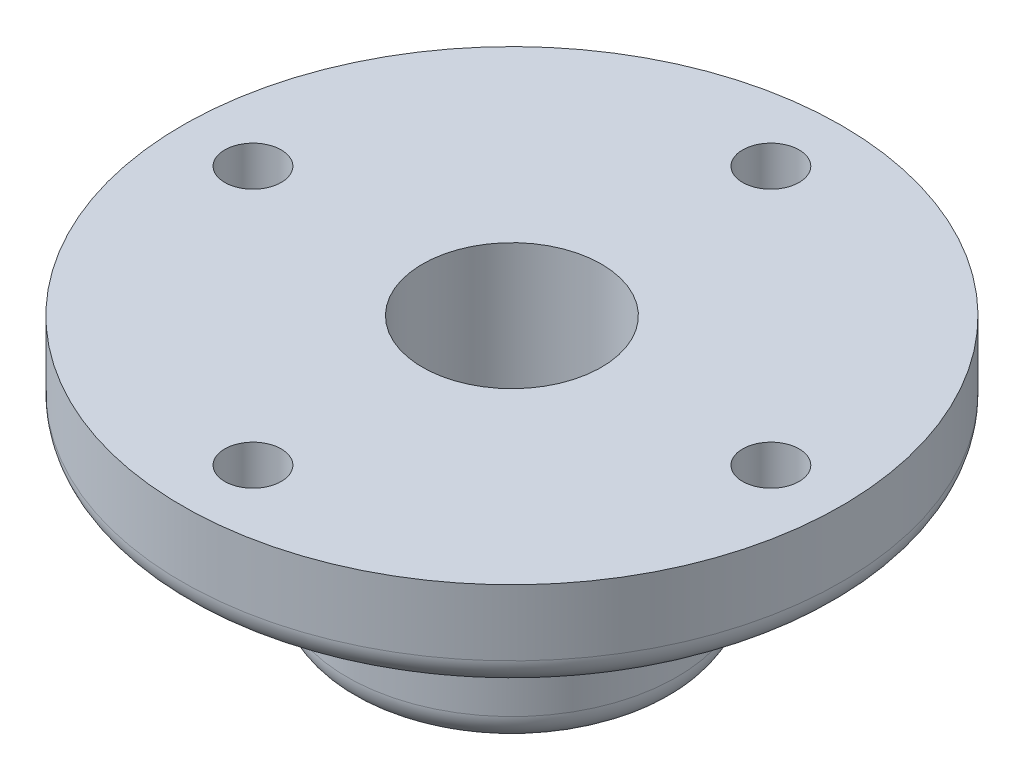
SolidWorks part; units mm, degrees
material "1060 Alloy"
ref_plane "Front Plane" through (0, 0, 0) normal (0, 0, 1) x (1, 0, 0)
ref_plane "Top Plane" through (0, 0, 0) normal (0, 1, 0) x (1, 0, 0)
ref_plane "Right Plane" through (0, 0, 0) normal (1, 0, 0) x (0, 0, -1)
sketch "Sketch1" plane through (0, 0, 0) normal (0, 0, 1) x (1, 0, 0)
  line L0 (0, 0) -> (10, 0)
  line L1 (16, 6) -> (16, 29)
  line L2 (22, 35) -> (45, 35)
  line L3 (51, 41) -> (51, 55)
  line L4 (51, 55) -> (0, 55)
  line L5 (0, 55) -> (0, 0)
  line L6 (-19, -10.4647) -> (-19, 33.6081) construction
  arc A0 (10, 0) -> (16, 6) centre (10, 6) ccw
  arc A1 (16, 29) -> (22, 35) centre (22, 29) cw
  arc A2 (45, 35) -> (51, 41) centre (45, 41) ccw
  point P12 (16, 0)
  point P17 (51, 35)
  dimension "D5" = 6
  dimension "D7" = 6
  dimension "D8" = 6
  dimension "D1" = 38
  dimension "D2" = 70
  dimension "D3" = 55
  dimension "D4" = 140
  dimension "D6" = 20
revolve "Revolve2" add sketch "Sketch1" angle 360 about L6
sketch "Sketch2" plane through (0, 55, 0) normal (0, 1, 0) x (1, 0, 0)
  circle A0 centre (-19, 0) radius 55 construction
  circle A1 centre (-19, 55) radius 6
  circle A2 centre (-74, 0) radius 6
  circle A3 centre (-19, -55) radius 6
  circle A4 centre (36, 0) radius 6
  circle A5 centre (-19, 0) radius 70 construction
  point P7 (0, 0)
  point P14 (-19, 0)
  point P15 (-19, 0)
  dimension "D1" = 110
  dimension "D2" = 12
  dimension "D3" = 4
extrude "Cut-Extrude1" cut sketch "Sketch2" against normal through all
